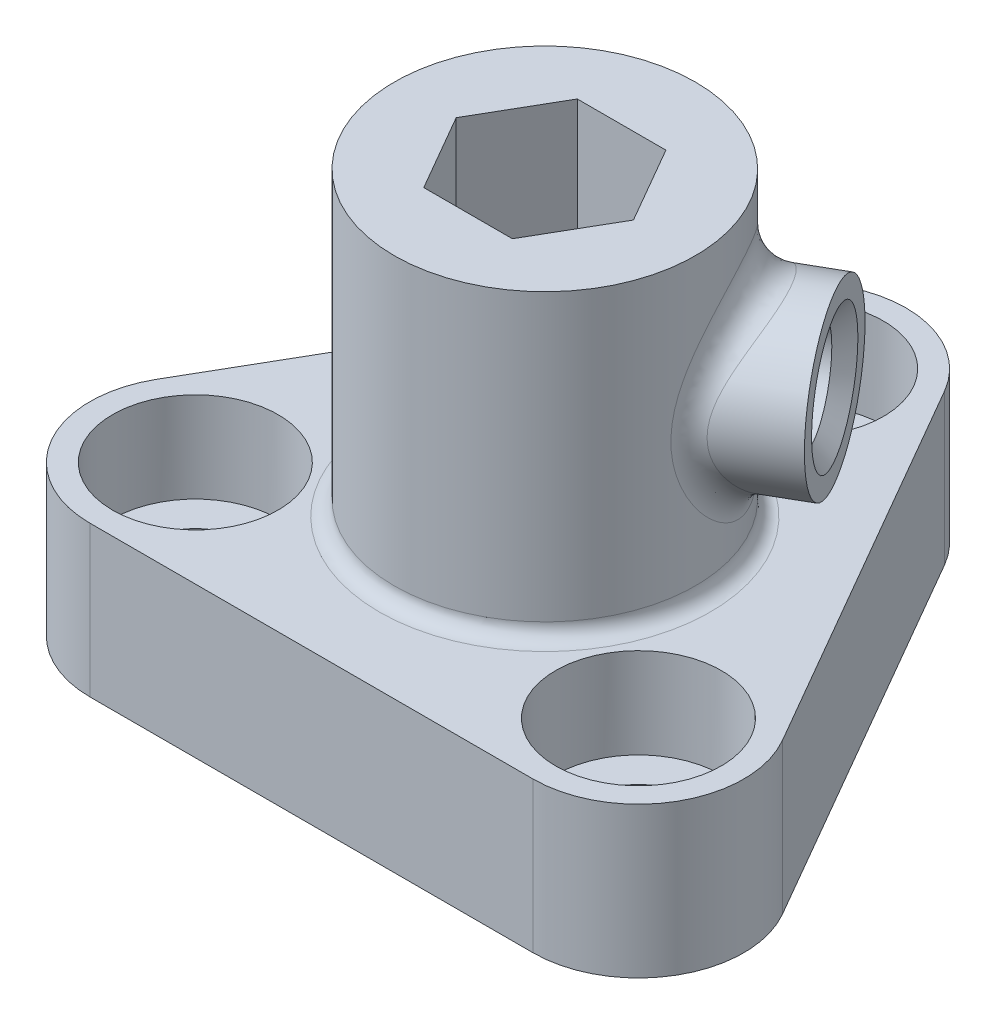
SolidWorks part; units mm, degrees
ref_plane "Front Plane" through (0, 0, 0) normal (0, 0, 1) x (1, 0, 0)
ref_plane "Top Plane" through (0, 0, 0) normal (0, 1, 0) x (1, 0, 0)
ref_plane "Right Plane" through (0, 0, 0) normal (1, 0, 0) x (0, 0, -1)
sketch "Sketch1" plane through (0, 0, 0) normal (1, 0, 0) x (0, 0, -1)
  line L1 (0, 0) -> (12, 0)
  line L2 (0, 0) -> (0, 5.3535)
  line L3 (5, 5) -> (12, 5)
  line L4 (12, 0) -> (12, 5)
  line L6 (0, 5.3535) -> (0, 15)
  line L7 (0, 15) -> (5, 15)
  line L8 (5, 5) -> (5, 15)
  dimension "D1" = 15
  dimension "6" = 5
  dimension "D3" = 5
  dimension "D4" = 7
revolve "Revolve1" add sketch "Sketch1" angle 360 about L6
sketch "Sketch4" plane through (0, 5, 0) normal (0, 1, 0) x (1, 0, 0)
  circle A0 centre (0, 8.5) radius 2.75
  circle A1 centre (7.3612, -4.25) radius 2.75
  circle A2 centre (-7.3612, -4.25) radius 2.75
  circle A6 centre (0, 0) radius 8.5 construction
  point P15 (0, 0)
  dimension "D2" = 17
  dimension "D3" = 5.5
  dimension "D1" = 3
extrude "Cut-Extrude4" cut sketch "Sketch4" against normal offset from surface (3 mm away) 2 up to face at (0, 0, -12)
sketch "Sketch5" plane through (0, 5, 0) normal (0, 1, 0) x (1, 0, 0)
  line L0 (-3.0311, 10.25) -> (-10.3923, -2.5)
  line L1 (-7.3612, -7.75) -> (7.3612, -7.75)
  line L2 (3.0311, 10.25) -> (10.3923, -2.5)
  arc A0 (3.0311, 10.25) -> (-3.0311, 10.25) centre (0, 8.5) ccw
  arc A1 (7.3612, -7.75) -> (10.3923, -2.5) centre (7.3612, -4.25) ccw
  arc A2 (-10.3923, -2.5) -> (-7.3612, -7.75) centre (-7.3612, -4.25) ccw
  circle A3 centre (0, 0) radius 12 construction
extrude "Cut-Extrude5" cut sketch "Sketch5" against normal through all flip side to cut
sketch "Sketch2" plane through (0, 15, 0) normal (0, 1, 0) x (1, 0, 0)
  line L0 (10.3923, -2.5) -> (3.0311, 10.25) construction
  line L1 (2.9445, 0) -> (1.4722, 2.55)
  line L2 (1.4722, 2.55) -> (-1.4722, 2.55)
  line L3 (-1.4722, 2.55) -> (-2.9445, 0)
  line L4 (-2.9445, 0) -> (-1.4722, -2.55)
  line L5 (-1.4722, -2.55) -> (1.4722, -2.55)
  line L6 (1.4722, -2.55) -> (2.9445, 0)
  circle A0 centre (0, 0) radius 2.55 construction
  dimension "D1" = 5.1
extrude "Cut-Extrude2" cut sketch "Sketch2" against normal up to surface (10 mm away) up to face at (0, 5, -5.75)
ref_plane "Plane1" through (6.1055, 0, -3.525) normal (-0.866, 0, 0.5) x (0.5, 0, 0.866)
sketch "Sketch3" plane through (6.1055, 0, -3.525) normal (0.866, 0, -0.5) x (-0.5, 0, -0.866)
  line L0 (0, 15) -> (0, 5) construction
  line L1 (1.4722, 15) -> (-1.4722, 15) construction
  line L3 (5, 5) -> (-5, 5) construction
  circle A0 centre (0, 10) radius 2.75
  point P10 (0, 10)
  dimension "D1" = 5.5
extrude "Boss-Extrude1" add sketch "Sketch3" against normal up to next
sketch "Sketch6" plane through (6.1055, 0, -3.525) normal (0.866, 0, -0.5) x (-0.5, 0, -0.866)
  circle A0 centre (0, 10) radius 1.6
  dimension "D1" = 3.2
extrude "Cut-Extrude6" cut sketch "Sketch6" against normal up to next
fillet "Fillet1" radius 0.5 1 edges at (0, 5, -5)
chamfer "Chamfer1" distance 0.5 angle 45 1 edges at (5.3055, 10, -4.9106)
fillet "Fillet2" radius 1 1 edges at (4.9921, 9.766, 0.2817)
sketch "Sketch7" plane through (0, 5, 0) normal (0, 1, 0) x (1, 0, 0)
  circle A0 centre (0, 8.5) radius 1.55
  circle A1 centre (7.3612, -4.25) radius 1.55
  circle A2 centre (-7.3612, -4.25) radius 1.55
  dimension "D1" = 3.1
extrude "Cut-Extrude7" cut sketch "Sketch7" against normal through all
